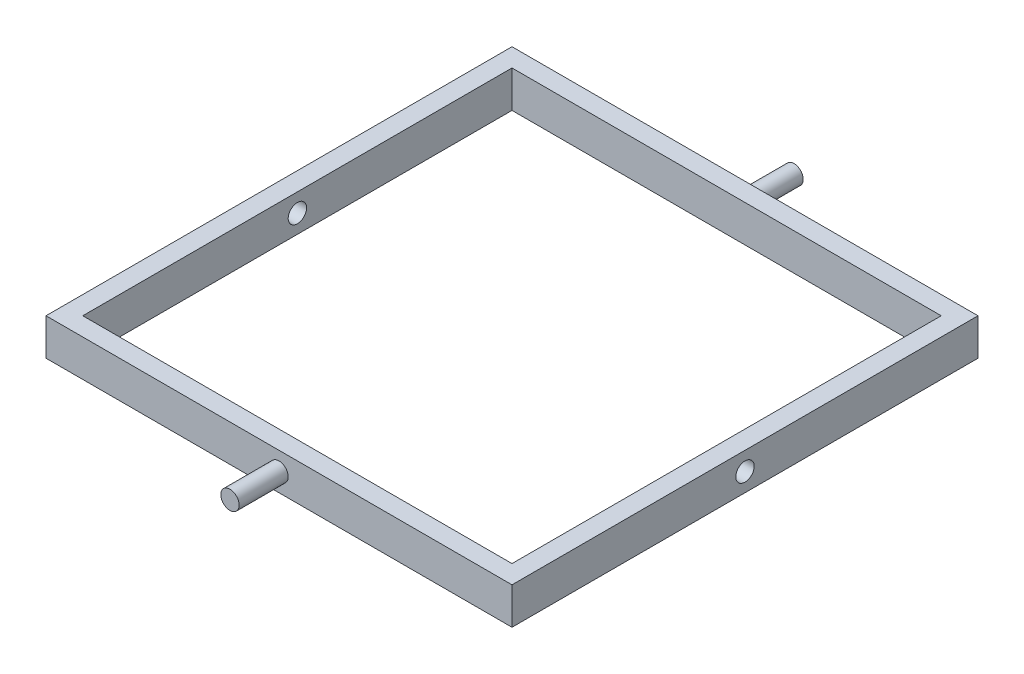
SolidWorks part; units mm, degrees
ref_plane "Front Plane" through (0, 0, 0) normal (0, 0, 1) x (1, 0, 0)
ref_plane "Top Plane" through (0, 0, 0) normal (0, 1, 0) x (1, 0, 0)
ref_plane "Right Plane" through (0, 0, 0) normal (1, 0, 0) x (0, 0, -1)
sketch "Sketch1" plane through (0, 0, 0) normal (0, 1, 0) x (1, 0, 0)
  line L0 (0.193, 35) -> (-0.193, -35) construction
  line L1 (-35.193, -35) -> (34.807, -35)
  line L2 (-35.193, -35) -> (-35.193, 35)
  line L3 (-35.193, 35) -> (34.807, 35)
  line L4 (34.807, -35) -> (34.807, 35)
  dimension "D1" = 70
  dimension "D2" = 70
extrude "Extrude-Thin1" add sketch "Sketch1" along normal blind 6 thin
sketch "Sketch2" plane through (34.807, 0, 0) normal (-1, 0, 0) x (0, 0, 1)
  line L0 (-35, 3) -> (35, 3) construction
  line L1 (-35, 6) -> (-35, 0) construction
  line L2 (35, 6) -> (35, 0) construction
  circle A0 centre (0, 3) radius 1.5
  point P8 (0, 0)
  dimension "D1" = 3
extrude "Cut-Extrude1" cut sketch "Sketch2" against normal through all both and the other way through all
sketch "Sketch3" plane through (0, 0, -38) normal (0, 0, -1) x (-1, 0, 0)
  line L0 (-37.807, 3) -> (38.193, 3) construction
  line L1 (-37.807, 6) -> (-37.807, 0) construction
  line L2 (38.193, 6) -> (38.193, 0) construction
  circle A0 centre (0.193, 3) radius 1.5
  point P8 (0, 0)
  dimension "D1" = 3
extrude "Boss-Extrude1" add sketch "Sketch3" along normal blind 8
mirror "Mirror1" about plane through (0, 0, 0) normal (0, 0, 1) of "Boss-Extrude1"
